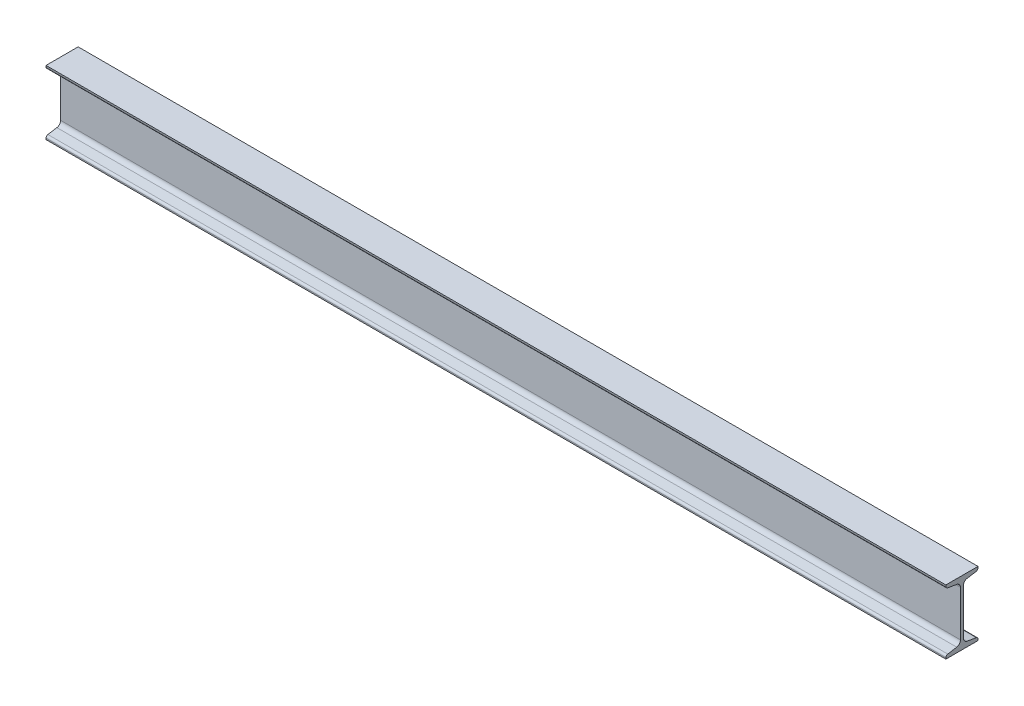
SolidWorks part; units mm, degrees
ref_plane "Alzado" through (0, 0, 0) normal (0, 0, 1) x (1, 0, 0)
ref_plane "Planta" through (0, 0, 0) normal (0, 1, 0) x (1, 0, 0)
ref_plane "Vista lateral" through (0, 0, 0) normal (1, 0, 0) x (0, 0, -1)
sketch "Croquis1" plane through (0, 0, 0) normal (0, 0, 1) x (1, 0, 0)
  line L0 (0, 0) -> (1400, 0)
  dimension "D1" = 1400
other "Viga sb 100 X 8(2)"
ref_plane "Plano2" through (0, 0, 0) normal (1, 0, 0) x (0, 0, 1)
sketch "Sketch14" plane through (0, 0, 0) normal (1, 0, 0) x (0, 0, 1)
  line L0 (-25, -50) -> (-25, -48.0607)
  line L1 (-22.0754, -44.6083) -> (-8.0991, -42.2787)
  line L2 (-2.25, -35.374) -> (-2.25, 35.374)
  line L3 (-8.0991, 42.2787) -> (-22.0754, 44.6083)
  line L4 (-25, 48.0607) -> (-25, 50)
  line L5 (-25, 50) -> (25, 50)
  line L6 (25, 50) -> (25, 48.0607)
  line L7 (22.0754, 44.6083) -> (8.0991, 42.2787)
  line L8 (2.25, 35.374) -> (2.25, -35.374)
  line L9 (8.0991, -42.2787) -> (22.0754, -44.6083)
  line L10 (25, -48.0607) -> (25, -50)
  line L11 (25, -50) -> (-25, -50)
  line L15 (-2.25, 0) -> (2.25, 0) construction
  arc A0 (-8.0991, -42.2787) -> (-2.25, -35.374) centre (-9.25, -35.374) ccw
  arc A1 (-2.25, 35.374) -> (-8.0991, 42.2787) centre (-9.25, 35.374) ccw
  arc A2 (8.0991, 42.2787) -> (2.25, 35.374) centre (9.25, 35.374) ccw
  arc A3 (2.25, -35.374) -> (8.0991, -42.2787) centre (9.25, -35.374) ccw
  arc A4 (-22.0754, 44.6083) -> (-25, 48.0607) centre (-21.5, 48.0607) cw
  arc A5 (22.0754, 44.6083) -> (25, 48.0607) centre (21.5, 48.0607) ccw
  arc A6 (-25, -48.0607) -> (-22.0754, -44.6083) centre (-21.5, -48.0607) cw
  arc A7 (25, -48.0607) -> (22.0754, -44.6083) centre (21.5, -48.0607) ccw
  point P1 (0, 50)
  point P8 (0, -50)
  point P21 (0, 0)
  point P34 (0, 0)
  dimension "RI" = 7
  dimension "D3" = 3.5
  dimension "BF" = 50
  dimension "D2" = 9.463
  dimension "DEPTH" = 100
  dimension "TW" = 4.5
  dimension "D1" = 70.748
